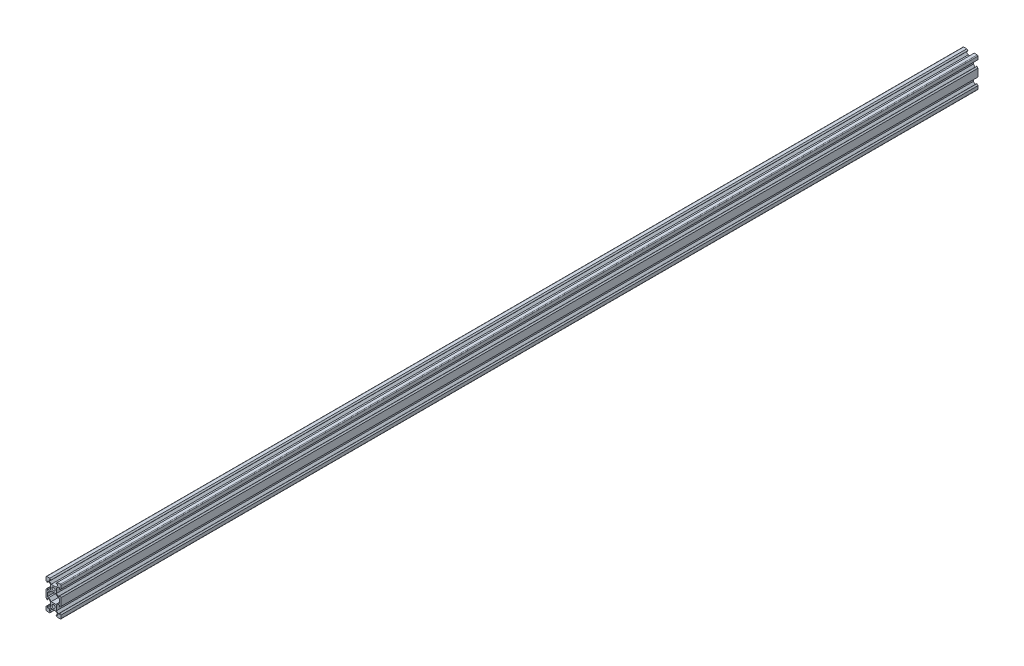
SolidWorks part; units mm, degrees
ref_plane "Front Plane" through (0, 0, 0) normal (0, 0, 1) x (1, 0, 0)
ref_plane "Top Plane" through (0, 0, 0) normal (0, 1, 0) x (1, 0, 0)
ref_plane "Right Plane" through (0, 0, 0) normal (1, 0, 0) x (0, 0, -1)
sketch "Sketch1" plane through (0, 0, 0) normal (0, 1, 0) x (1, 0, 0)
  line L0 (0, -610) -> (0, 610)
  point P4 (0, 0)
  dimension "D1" = 1220
other "Vslot2040 2040(1)"
ref_plane "Plane1" through (0, 0, 610) normal (0, 0, -1) x (-1, 0, 0)
sketch "Sketch11" plane through (0, 0, 610) normal (0, 0, -1) x (-1, 0, 0)
  line L12 (3.125, 6.1) -> (6.275, 2.95)
  line L13 (6.275, 2.95) -> (8.2, 2.95)
  line L14 (8.2, 2.95) -> (8.2, -2.95)
  line L15 (8.2, -2.95) -> (6.275, -2.95)
  line L16 (3.125, -6.1) -> (6.275, -2.95)
  line L17 (3.125, -6.1) -> (-3.125, -6.1)
  line L18 (-3.125, -6.1) -> (-6.275, -2.95)
  line L19 (-8.2, -2.95) -> (-6.275, -2.95)
  line L20 (-8.2, 2.95) -> (-8.2, -2.95)
  line L21 (-6.275, 2.95) -> (-8.2, 2.95)
  line L22 (-3.125, 6.1) -> (-6.275, 2.95)
  line L23 (3.125, 6.1) -> (-3.125, 6.1)
  line L128 (5.5, -18.2) -> (3.6078, -18.2)
  line L129 (3.4664, -18.5414) -> (4.925, -20)
  line L130 (4.925, -20) -> (9, -20)
  line L131 (10, -19) -> (10, -14.925)
  line L132 (10, -14.925) -> (8.5414, -13.4664)
  line L133 (8.2, -13.6078) -> (8.2, -15.5)
  line L134 (8.2, -15.5) -> (6.275, -15.5)
  line L135 (6.275, -15.5) -> (3.9, -13.125)
  line L136 (3.9, -13.125) -> (3.9, -6.875)
  line L137 (3.9, -6.875) -> (6.275, -4.5)
  line L138 (6.275, -4.5) -> (8.2, -4.5)
  line L139 (8.2, -4.5) -> (8.2, -6.3922)
  line L140 (8.5414, -6.5336) -> (10, -5.075)
  line L141 (10, -5.075) -> (10, 5.075)
  line L142 (10, 5.075) -> (8.5414, 6.5336)
  line L143 (8.2, 6.3922) -> (8.2, 4.5)
  line L144 (8.2, 4.5) -> (6.275, 4.5)
  line L145 (6.275, 4.5) -> (3.9, 6.875)
  line L146 (3.9, 6.875) -> (3.9, 13.125)
  line L147 (3.9, 13.125) -> (6.275, 15.5)
  line L148 (6.275, 15.5) -> (8.2, 15.5)
  line L149 (8.2, 15.5) -> (8.2, 13.6078)
  line L150 (8.5414, 13.4664) -> (10, 14.925)
  line L151 (10, 14.925) -> (10, 19)
  line L152 (9, 20) -> (4.925, 20)
  line L153 (4.925, 20) -> (3.4664, 18.5414)
  line L154 (3.6078, 18.2) -> (5.5, 18.2)
  line L155 (5.5, 18.2) -> (5.5, 16.275)
  line L156 (5.5, 16.275) -> (3.125, 13.9)
  line L157 (3.125, 13.9) -> (-3.125, 13.9)
  line L158 (-3.125, 13.9) -> (-5.5, 16.275)
  line L159 (-5.5, 16.275) -> (-5.5, 18.2)
  line L160 (-5.5, 18.2) -> (-3.6078, 18.2)
  line L161 (-3.4664, 18.5414) -> (-4.925, 20)
  line L162 (-4.925, 20) -> (-9, 20)
  line L163 (-10, 19) -> (-10, 14.925)
  line L164 (-10, 14.925) -> (-8.5414, 13.4664)
  line L165 (-8.2, 13.6078) -> (-8.2, 15.5)
  line L166 (-8.2, 15.5) -> (-6.275, 15.5)
  line L167 (-6.275, 15.5) -> (-3.9, 13.125)
  line L168 (-3.9, 13.125) -> (-3.9, 6.875)
  line L169 (-3.9, 6.875) -> (-6.275, 4.5)
  line L170 (-6.275, 4.5) -> (-8.2, 4.5)
  line L171 (-8.2, 4.5) -> (-8.2, 6.3922)
  line L172 (-8.5414, 6.5336) -> (-10, 5.075)
  line L173 (-10, 5.075) -> (-10, -5.075)
  line L174 (-10, -5.075) -> (-8.5414, -6.5336)
  line L175 (-8.2, -6.3922) -> (-8.2, -4.5)
  line L176 (-8.2, -4.5) -> (-6.275, -4.5)
  line L177 (-6.275, -4.5) -> (-3.9, -6.875)
  line L178 (-3.9, -6.875) -> (-3.9, -13.125)
  line L179 (-3.9, -13.125) -> (-6.275, -15.5)
  line L180 (-6.275, -15.5) -> (-8.2, -15.5)
  line L181 (-8.2, -15.5) -> (-8.2, -13.6078)
  line L182 (-8.5414, -13.4664) -> (-10, -14.925)
  line L183 (-10, -14.925) -> (-10, -19)
  line L184 (-9, -20) -> (-4.925, -20)
  line L185 (-4.925, -20) -> (-3.4664, -18.5414)
  line L186 (-3.6078, -18.2) -> (-5.5, -18.2)
  line L187 (-5.5, -18.2) -> (-5.5, -16.275)
  line L188 (-5.5, -16.275) -> (-3.125, -13.9)
  line L189 (-3.125, -13.9) -> (3.125, -13.9)
  line L190 (3.125, -13.9) -> (5.5, -16.275)
  line L191 (5.5, -16.275) -> (5.5, -18.2)
  circle A2 centre (0, -10) radius 2.1
  circle A3 centre (0, 10) radius 2.1
  arc A32 (3.6078, -18.2) -> (3.4664, -18.5414) centre (3.6078, -18.4) ccw
  arc A33 (9, -20) -> (10, -19) centre (9, -19) ccw
  arc A34 (8.5414, -13.4664) -> (8.2, -13.6078) centre (8.4, -13.6078) ccw
  arc A35 (8.2, -6.3922) -> (8.5414, -6.5336) centre (8.4, -6.3922) ccw
  arc A36 (8.5414, 6.5336) -> (8.2, 6.3922) centre (8.4, 6.3922) ccw
  arc A37 (8.2, 13.6078) -> (8.5414, 13.4664) centre (8.4, 13.6078) ccw
  arc A38 (10, 19) -> (9, 20) centre (9, 19) ccw
  arc A39 (3.4664, 18.5414) -> (3.6078, 18.2) centre (3.6078, 18.4) ccw
  arc A40 (-3.6078, 18.2) -> (-3.4664, 18.5414) centre (-3.6078, 18.4) ccw
  arc A41 (-9, 20) -> (-10, 19) centre (-9, 19) ccw
  arc A42 (-8.5414, 13.4664) -> (-8.2, 13.6078) centre (-8.4, 13.6078) ccw
  arc A43 (-8.2, 6.3922) -> (-8.5414, 6.5336) centre (-8.4, 6.3922) ccw
  arc A44 (-8.5414, -6.5336) -> (-8.2, -6.3922) centre (-8.4, -6.3922) ccw
  arc A45 (-8.2, -13.6078) -> (-8.5414, -13.4664) centre (-8.4, -13.6078) ccw
  arc A46 (-10, -19) -> (-9, -20) centre (-9, -19) ccw
  arc A47 (-3.4664, -18.5414) -> (-3.6078, -18.2) centre (-3.6078, -18.4) ccw
  point P43 (0, 0)
